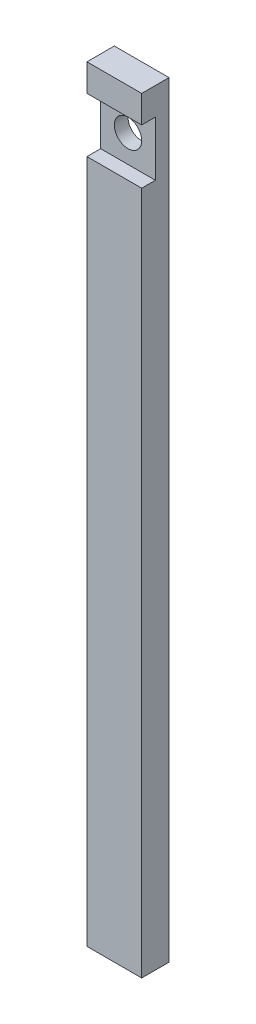
SolidWorks part; units mm, degrees
ref_plane "Front Plane" through (0, 0, 0) normal (0, 0, 1) x (1, 0, 0)
ref_plane "Top Plane" through (0, 0, 0) normal (0, 1, 0) x (1, 0, 0)
ref_plane "Right Plane" through (0, 0, 0) normal (1, 0, 0) x (0, 0, -1)
sketch "Sketch1" plane through (0, 0, 0) normal (0, 1, 0) x (1, 0, 0)
  line L1 (0, 0) -> (25.4, 0)
  line L2 (0, 0) -> (0, 12.7)
  line L3 (0, 12.7) -> (25.4, 12.7)
  line L4 (25.4, 0) -> (25.4, 12.7)
  dimension "D1" = 25.4
  dimension "D2" = 12.7
extrude "Boss-Extrude1" add sketch "Sketch1" along normal blind 355.6
sketch "Sketch2" plane through (25.4, 0, 0) normal (1, 0, 0) x (0, 0, -1)
  line L0 (0, 355.6) -> (0, 0) construction
  line L1 (0, 342.9) -> (6.35, 342.9)
  line L2 (0, 342.9) -> (0, 317.5)
  line L3 (0, 317.5) -> (6.35, 317.5)
  line L4 (6.35, 342.9) -> (6.35, 317.5)
  line L5 (0, 0) -> (12.7, 0) construction
  dimension "D1" = 6.35
  dimension "D2" = 25.4
  dimension "D3" = 317.5
extrude "Cut-Extrude1" cut sketch "Sketch2" against normal through all
sketch "Sketch3" plane through (0, 0, -6.35) normal (0, 0, 1) x (1, 0, 0)
  line L0 (0, 355.6) -> (25.4, 355.6) construction
  line L1 (25.4, 317.5) -> (25.4, 342.9) construction
  circle A0 centre (12.7, 330.2) radius 6.35
  point P4 (12.7, 355.6)
  point P7 (25.4, 330.2)
  dimension "D1" = 12.7
extrude "Cut-Extrude2" cut sketch "Sketch3" against normal through all
sketch "Sketch4" plane through (0, 0, 0) normal (0, -1, 0) x (1, 0, 0)
  line L0 (0, -12.7) -> (0, 0) construction
  circle A0 centre (6.35, -6.35) radius 3.175
  circle A1 centre (19.05, -6.35) radius 3.175
  point P6 (0, -6.35)
  dimension "D1" = 6.35
  dimension "D2" = 6.35
  dimension "D3" = 12.7
extrude "Cut-Extrude3" cut sketch "Sketch4" against normal blind 25.4
